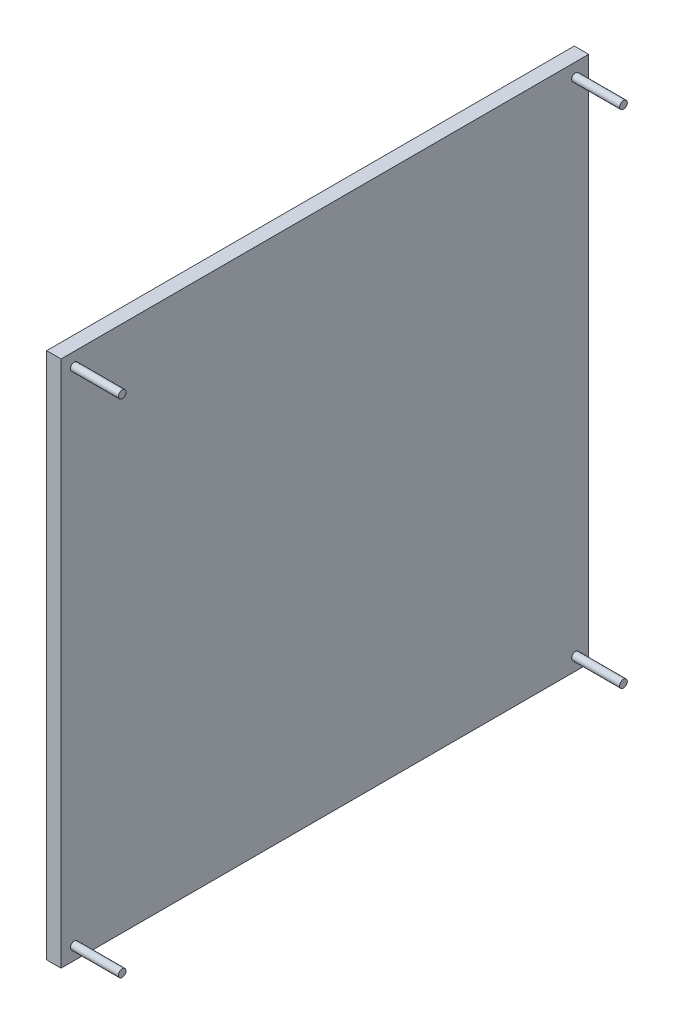
SolidWorks part; units mm, degrees
ref_plane "前视基准面" through (0, 0, 0) normal (0, 0, 1) x (1, 0, 0)
ref_plane "上视基准面" through (0, 0, 0) normal (0, 1, 0) x (1, 0, 0)
ref_plane "右视基准面" through (0, 0, 0) normal (1, 0, 0) x (0, 0, -1)
sketch "草图1" plane through (0, 0, 0) normal (1, 0, 0) x (0, 0, -1)
  line L22 (86.7954, 125.4242) -> (-133.2046, 125.4242)
  line L23 (86.7954, 125.4242) -> (86.7954, -94.5758)
  line L24 (86.7954, -94.5758) -> (-133.2046, -94.5758)
  line L25 (-133.2046, 125.4242) -> (-133.2046, -94.5758)
  circle A16 centre (81.2954, 119.9242) radius 1.6
  circle A17 centre (-127.7046, 119.9242) radius 1.6
  circle A18 centre (-127.7046, -89.0758) radius 1.6
  circle A19 centre (81.2954, -89.0758) radius 1.6
  dimension "D68" = 3.2
  dimension "D69" = 3.2
  dimension "D70" = 3.2
  dimension "D71" = 3.2
  dimension "D64" = 220
  dimension "D65" = 220
  dimension "D72" = 209
  dimension "D73" = 209
  dimension "D74" = 209
  dimension "D75" = 209
  dimension "D76" = 5.5
  dimension "D77" = 5.5
  dimension "D78" = 5.5
  dimension "D79" = 5.5
extrude "凸台-拉伸1" add sketch "草图1" along normal blind 6
sketch "草图2" plane through (6, 0, 0) normal (1, 0, 0) x (0, 0, -1)
  circle A0 centre (81.2954, -89.0758) radius 1.6 construction
  circle A1 centre (-127.7046, -89.0758) radius 1.6 construction
  circle A2 centre (81.2954, 119.9242) radius 1.6 construction
  circle A3 centre (-127.7046, 119.9242) radius 1.6 construction
  circle A4 centre (81.2954, -89.0758) radius 1.6
  circle A5 centre (-127.7046, -89.0758) radius 1.6
  circle A6 centre (81.2954, 119.9242) radius 1.6
  circle A7 centre (-127.7046, 119.9242) radius 1.6
extrude "凸台-拉伸2" add sketch "草图2" along normal blind 20 and the other way blind 6
